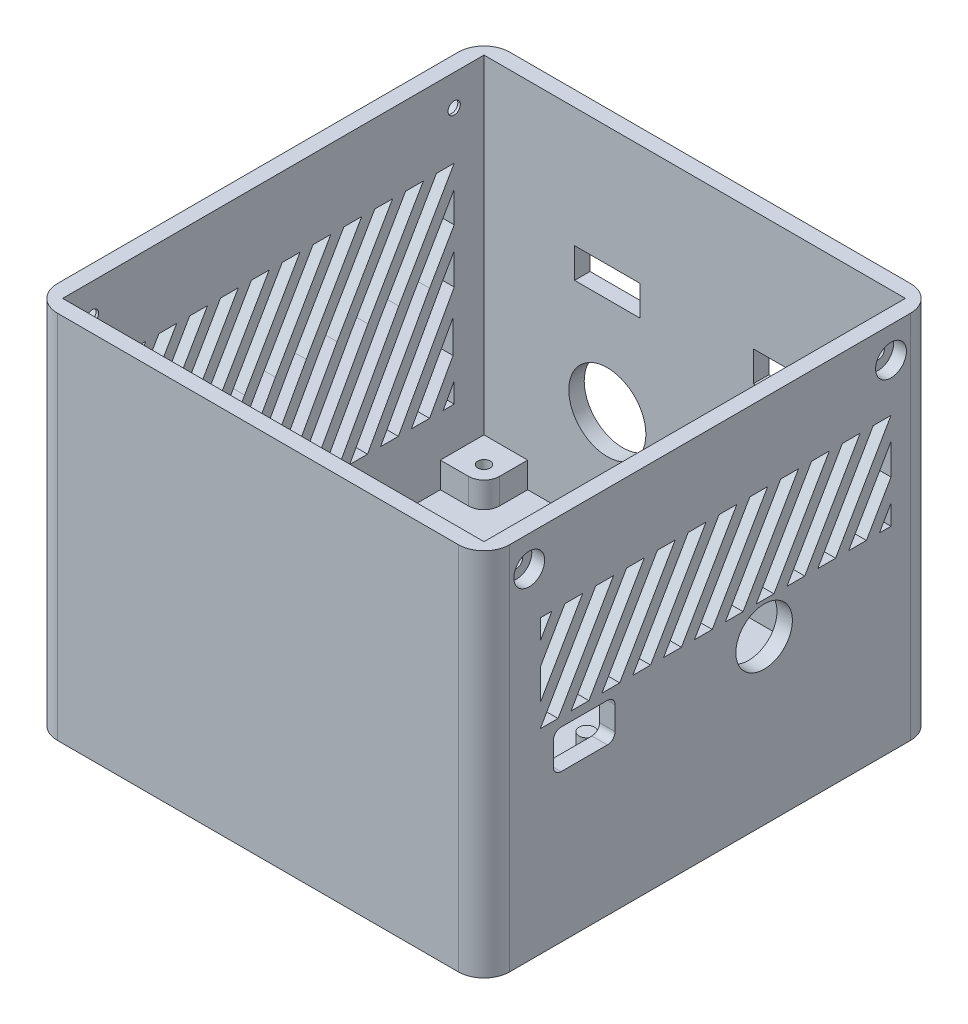
SolidWorks part; units mm, degrees
ref_plane "前基準面" through (0, 0, 0) normal (0, 0, 1) x (1, 0, 0)
ref_plane "上基準面" through (0, 0, 0) normal (0, 1, 0) x (1, 0, 0)
ref_plane "右基準面" through (0, 0, 0) normal (1, 0, 0) x (0, 0, -1)
sketch "草圖1" plane through (0, 0, 0) normal (0, 1, 0) x (1, 0, 0)
  line L5 (-40.3185, 48.6228) -> (47.6815, 48.6228)
  line L6 (-40.3185, 48.6228) -> (-40.3185, -39.3772)
  line L7 (-40.3185, -39.3772) -> (47.6815, -39.3772)
  line L8 (47.6815, 48.6228) -> (47.6815, -39.3772)
  dimension "D1" = 88
  dimension "D2" = 88
extrude "填料-伸長1" add sketch "草圖1" along normal blind 3
sketch "草圖2" plane through (0, 3, 0) normal (0, 1, 0) x (1, 0, 0)
  line L0 (-40.3185, 48.6228) -> (47.6815, 48.6228)
  line L1 (47.6815, 48.6228) -> (47.6815, -39.3772)
  line L2 (47.6815, -39.3772) -> (-40.3185, -39.3772)
  line L3 (-40.3185, -39.3772) -> (-40.3185, 48.6228)
  line L4 (-37.3185, 45.6228) -> (-37.3185, -36.3772)
  line L5 (-37.3185, -36.3772) -> (44.6815, -36.3772)
  line L6 (44.6815, -36.3772) -> (44.6815, 45.6228)
  line L7 (44.6815, 45.6228) -> (-37.3185, 45.6228)
  dimension "D1" = 3
  dimension "D2" = 3
  dimension "D3" = 3
  dimension "D4" = 3
extrude "填料-伸長2" add sketch "草圖2" along normal blind 69
sketch "草圖3" plane through (0, 3, 0) normal (0, 1, 0) x (1, 0, 0)
  line L0 (44.6815, 45.6228) -> (-37.3185, 45.6228) construction
  line L5 (-37.3185, -36.3772) -> (-28.8185, -36.3772)
  line L6 (-37.3185, -36.3772) -> (-37.3185, -27.8772)
  line L7 (-37.3185, -27.8772) -> (-28.8185, -27.8772)
  line L8 (-28.8185, -36.3772) -> (-28.8185, -27.8772)
  line L9 (44.6815, 45.6228) -> (36.1815, 45.6228)
  line L10 (44.6815, 45.6228) -> (44.6815, 37.1228)
  line L11 (44.6815, 37.1228) -> (36.1815, 37.1228)
  line L12 (36.1815, 45.6228) -> (36.1815, 37.1228)
  line L15 (44.6815, -19.3772) -> (36.1815, -19.3772)
  line L16 (36.1815, -27.8772) -> (36.1815, -19.3772)
  line L17 (-37.3185, 45.6228) -> (-37.3185, -36.3772) construction
  line L18 (36.1815, -27.8772) -> (44.6815, -27.8772)
  line L23 (-37.3185, 45.6228) -> (-28.8185, 45.6228)
  line L24 (-37.3185, 45.6228) -> (-37.3185, 37.1228)
  line L25 (-37.3185, 37.1228) -> (-28.8185, 37.1228)
  line L26 (-28.8185, 45.6228) -> (-28.8185, 37.1228)
  line L27 (44.6815, -36.3772) -> (44.6815, 45.6228) construction
  line L28 (44.6815, -27.8772) -> (44.6815, -19.3772)
  circle A0 centre (-17.3185, 25.6228) radius 1.5
  circle A1 centre (2.6815, 25.6228) radius 1.5
  circle A2 centre (22.6815, 25.6228) radius 1.5
  circle A4 centre (22.6815, 5.6228) radius 1.5
  circle A5 centre (2.6815, -14.3772) radius 1.5
  circle A6 centre (22.6815, -14.3772) radius 1.5
  circle A7 centre (-17.3185, 5.6228) radius 1.5
  circle A8 centre (-17.3185, -14.3772) radius 1.5
  circle A9 centre (2.6815, 5.6228) radius 1.5 [skipped]
  circle A10 centre (2.6815, 15.6376) radius 1.5
  dimension "D9" = 3
  dimension "D14" = 3
  dimension "D15" = 40
  dimension "D2" = 8.5
  dimension "D3" = 8.5
  dimension "D4" = 8.5
  dimension "D5" = 8.5
  dimension "D6" = 8.5
  dimension "D7" = 8.5
  dimension "D8" = 8.5
  dimension "D10" = 20
  dimension "D11" = 20
  dimension "D16" = 8.5
  dimension "D12" = 3
  dimension "D13" = 3
extrude "填料-伸長3" add sketch "草圖3" along normal blind 5
sketch "草圖4" plane through (0, 8, 0) normal (0, 1, 0) x (1, 0, 0)
  line L0 (-37.3185, 45.6228) -> (-37.3185, -36.3772) construction
  line L1 (44.6815, 45.6228) -> (-37.3185, 45.6228) construction
  line L2 (-37.3185, -36.3772) -> (44.6815, -36.3772) construction
  line L4 (44.6815, -19.3772) -> (44.6815, 37.1228) construction
  circle A1 centre (-32.3185, -31.3772) radius 1.2
  circle A3 centre (39.6815, 40.6228) radius 1.2
  circle A5 centre (39.6815, -23.3772) radius 1.2
  circle A6 centre (-32.3185, 40.6228) radius 1.2
  dimension "D7" = 5
  dimension "D9" = 2.4
  dimension "D10" = 2.4
  dimension "D2" = 2.4
  dimension "D3" = 5
  dimension "D4" = 5
  dimension "D8" = 5
extrude "除料-伸長1" cut sketch "草圖4" against normal blind 6
fillet "圓角1" radius 5 4 edges at (47.6815, 36, -48.6228) (-40.3185, 36, 39.3772) (-40.3185, 36, -48.6228) (47.6815, 36, 39.3772)
sketch "草圖7" plane through (-40.3185, 0, 0) normal (-1, 0, 0) x (0, 0, 1)
  line L0 (-39.8228, 56.6826) -> (-29.0364, 38)
  line L1 (-39.8228, 56.6826) -> (-36.3587, 56.6826)
  line L2 (-29.0364, 38) -> (-25.5723, 38)
  line L3 (-36.3587, 56.6826) -> (-25.5723, 38)
  line L4 (-48.6228, 0) -> (-48.6228, 72) construction
  line L5 (-33.8228, 56.6826) -> (-23.0364, 38)
  line L6 (-33.8228, 56.6826) -> (-30.3587, 56.6826)
  line L7 (-30.3587, 56.6826) -> (-19.5723, 38)
  line L8 (-23.0364, 38) -> (-19.5723, 38)
  line L9 (-27.8228, 56.6826) -> (-17.0364, 38)
  line L10 (-27.8228, 56.6826) -> (-24.3587, 56.6826)
  line L11 (-24.3587, 56.6826) -> (-13.5723, 38)
  line L12 (-17.0364, 38) -> (-13.5723, 38)
  line L13 (-21.8228, 56.6826) -> (-11.0364, 38)
  line L14 (-21.8228, 56.6826) -> (-18.3587, 56.6826)
  line L15 (-18.3587, 56.6826) -> (-7.5723, 38)
  line L16 (-11.0364, 38) -> (-7.5723, 38)
  line L17 (-15.8228, 56.6826) -> (-5.0364, 38)
  line L18 (-15.8228, 56.6826) -> (-12.3587, 56.6826)
  line L19 (-12.3587, 56.6826) -> (-1.5723, 38)
  line L20 (-5.0364, 38) -> (-1.5723, 38)
  line L21 (-9.8228, 56.6826) -> (0.9636, 38)
  line L22 (-9.8228, 56.6826) -> (-6.3587, 56.6826)
  line L23 (-6.3587, 56.6826) -> (4.4277, 38)
  line L24 (0.9636, 38) -> (4.4277, 38)
  line L25 (-3.8228, 56.6826) -> (6.9636, 38)
  line L26 (-3.8228, 56.6826) -> (-0.3587, 56.6826)
  line L27 (-0.3587, 56.6826) -> (10.4277, 38)
  line L28 (6.9636, 38) -> (10.4277, 38)
  line L29 (2.1772, 56.6826) -> (12.9636, 38)
  line L30 (2.1772, 56.6826) -> (5.6413, 56.6826)
  line L31 (5.6413, 56.6826) -> (16.4277, 38)
  line L32 (12.9636, 38) -> (16.4277, 38)
  line L33 (8.1772, 56.6826) -> (18.9636, 38)
  line L34 (8.1772, 56.6826) -> (11.6413, 56.6826)
  line L35 (11.6413, 56.6826) -> (22.4277, 38)
  line L36 (18.9636, 38) -> (22.4277, 38)
  line L37 (14.1772, 56.6826) -> (24.9636, 38)
  line L38 (14.1772, 56.6826) -> (17.6413, 56.6826)
  line L39 (17.6413, 56.6826) -> (28.4277, 38)
  line L40 (24.9636, 38) -> (28.4277, 38)
  line L52 (-35.0364, 38) -> (-31.5723, 38)
  line L57 (-39.8228, 46.2903) -> (-39.8228, 52.2903)
  line L58 (-39.8228, 46.2903) -> (-35.0364, 38)
  line L59 (-45.8228, 56.6826) -> (-35.0364, 38) [skipped]
  line L60 (-39.8228, 52.2903) -> (-31.5723, 38)
  line L61 (-42.3587, 56.6826) -> (-31.5723, 38) [skipped]
  line L62 (-45.8228, 56.6826) -> (-42.3587, 56.6826) [skipped]
  line L63 (-39.8228, 41.898) -> (-39.8228, 38)
  line L64 (-39.8228, 38) -> (-37.5723, 38)
  line L65 (-51.8228, 56.6826) -> (-41.0364, 38) [skipped]
  line L66 (-39.8228, 41.898) -> (-37.5723, 38)
  line L67 (28.4277, 42.3923) -> (28.4277, 48.3923)
  line L68 (-48.3587, 56.6826) -> (-37.5723, 38) [skipped]
  line L69 (-51.8228, 56.6826) -> (-48.3587, 56.6826) [skipped]
  line L70 (-41.0364, 38) -> (-37.5723, 38) [skipped]
  line L71 (28.4277, 48.3923) -> (23.6413, 56.6826)
  line L72 (20.1772, 56.6826) -> (28.4277, 42.3923)
  line L73 (20.1772, 56.6826) -> (23.6413, 56.6826)
  line L74 (20.1772, 56.6826) -> (30.9636, 38) [skipped]
  line L75 (30.9636, 38) -> (34.4277, 38) [skipped]
  line L76 (23.6413, 56.6826) -> (34.4277, 38) [skipped]
  line L77 (20.1772, 56.6826) -> (23.6413, 56.6826) [skipped]
  line L78 (28.4277, 52.7846) -> (28.4277, 56.6826)
  line L79 (28.4277, 56.6826) -> (26.1772, 56.6826)
  line L80 (26.1772, 56.6826) -> (28.4277, 52.7846)
  line L81 (26.1772, 56.6826) -> (36.9636, 38) [skipped]
  line L82 (36.9636, 38) -> (40.4277, 38) [skipped]
  line L83 (29.6413, 56.6826) -> (40.4277, 38) [skipped]
  line L84 (26.1772, 56.6826) -> (29.6413, 56.6826) [skipped]
  line L86 (-43.6228, 0) -> (34.3772, 0) construction
  dimension "D1" = 3
  dimension "D2" = 120
  dimension "D3" = 8.8
  dimension "D6" = 38
  dimension "D4" = 12
  dimension "D5" = 3
extrude "除料-伸長4" cut sketch "草圖7" against normal through all both and the other way through all
sketch "草圖8" plane through (0, 0, -48.6228) normal (0, 0, -1) x (-1, 0, 0)
  line L0 (-42.6815, 72) -> (-42.6815, 0) construction
  line L1 (-42.6815, 0) -> (35.3185, 0) construction
  line L2 (35.3185, 0) -> (35.3185, 72) construction
  line L3 (-42.6815, 72) -> (35.3185, 72) construction
  line L4 (-25.3665, 48.7) -> (-15.1165, 48.7)
  line L5 (-25.3665, 48.7) -> (-25.3665, 42.85)
  line L6 (-25.3665, 42.85) -> (-15.1165, 42.85)
  line L7 (-15.1165, 48.7) -> (-15.1165, 42.85)
  line L8 (6.9385, 48.7) -> (19.6885, 48.7)
  line L9 (6.9385, 48.7) -> (6.9385, 42.85)
  line L10 (6.9385, 42.85) -> (19.6885, 42.85)
  line L11 (19.6885, 48.7) -> (19.6885, 42.85)
  circle A0 centre (-20.2415, 24) radius 7.5
  circle A1 centre (13.3185, 23.82) radius 7.5
  point P18 (-15.1165, 45.775)
  point P19 (19.6885, 45.775)
  dimension "D2" = 15
  dimension "D3" = 24
  dimension "D4" = 22
  dimension "D5" = 23.82
  dimension "D6" = 15
  dimension "D11" = 5.125
  dimension "D1" = 22.44
  dimension "D7" = 5.85
  dimension "D8" = 5.85
  dimension "D9" = 10.25
  dimension "D10" = 12.75
  dimension "D12" = 6.38
  dimension "D13" = 23.3
  dimension "D14" = 23.3
extrude "除料-伸長5" cut sketch "草圖8" against normal up to next
sketch "草圖9" plane through (47.6815, 0, 0) normal (1, 0, 0) x (0, 0, -1)
  line L0 (43.6228, 0) -> (43.6228, 72) construction
  line L1 (-34.3772, 72) -> (43.6228, 72) construction
  circle A1 centre (15.1328, 31.75) radius 5.5
  dimension "D1" = 28.49
  dimension "D3" = 11
  dimension "D2" = 40.25
extrude "除料-伸長7" cut sketch "草圖9" against normal up to next
sketch "草圖11" plane through (47.6815, 0, 0) normal (1, 0, 0) x (0, 0, -1)
  line L6 (-34.3772, 72) -> (-34.3772, 0) construction
  line L7 (-24.3772, 36.25) -> (-15.3772, 36.25)
  line L8 (-25.8772, 34.75) -> (-25.8772, 30.25)
  line L9 (-24.3772, 28.75) -> (-15.3772, 28.75)
  line L10 (-13.8772, 34.75) -> (-13.8772, 30.25)
  line L11 (-34.3772, 0) -> (43.6228, 0) construction
  arc A4 (-15.3772, 36.25) -> (-13.8772, 34.75) centre (-15.3772, 34.75) cw
  arc A5 (-15.3772, 28.75) -> (-13.8772, 30.25) centre (-15.3772, 30.25) ccw
  arc A6 (-25.8772, 30.25) -> (-24.3772, 28.75) centre (-24.3772, 30.25) ccw
  arc A7 (-24.3772, 36.25) -> (-25.8772, 34.75) centre (-24.3772, 34.75) ccw
  point P10 (-15.3772, 30)
  point P15 (-24.3772, 30)
  point P18 (-15.3772, 35)
  point P28 (-13.8772, 28.75)
  point P31 (-25.8772, 28.75)
  point P34 (-25.8772, 36.25)
  dimension "D5" = 28.75
  dimension "D10" = 1.5
  dimension "D2" = 9
  dimension "D3" = 5
  dimension "D4" = 8.5
  dimension "D6" = 12
  dimension "D7" = 7.5
extrude "除料-伸長9" cut sketch "草圖11" against normal up to next
sketch "草圖12" plane through (-40.3185, 0, 0) normal (-1, 0, 0) x (0, 0, 1)
  line L0 (-35.0364, 38) -> (-22.9609, 16.0785)
  line L1 (-35.0364, 38) -> (-31.5723, 38)
  line L2 (-31.5723, 38) -> (-19.4968, 16.0785)
  line L3 (-19.4968, 16.0785) -> (-22.9609, 16.0785)
  line L4 (-13.4968, 16.0785) -> (-16.9609, 16.0785)
  line L5 (-29.0364, 38) -> (-16.9609, 16.0785)
  line L6 (-29.0364, 38) -> (-25.5723, 38)
  line L7 (-25.5723, 38) -> (-13.4968, 16.0785)
  line L8 (-7.4968, 16.0785) -> (-10.9609, 16.0785)
  line L9 (-23.0364, 38) -> (-10.9609, 16.0785)
  line L10 (-23.0364, 38) -> (-19.5723, 38)
  line L11 (-19.5723, 38) -> (-7.4968, 16.0785)
  line L12 (-1.4968, 16.0785) -> (-4.9609, 16.0785)
  line L13 (-17.0364, 38) -> (-4.9609, 16.0785)
  line L14 (-17.0364, 38) -> (-13.5723, 38)
  line L15 (-13.5723, 38) -> (-1.4968, 16.0785)
  line L16 (4.5032, 16.0785) -> (1.0391, 16.0785)
  line L17 (-11.0364, 38) -> (1.0391, 16.0785)
  line L18 (-11.0364, 38) -> (-7.5723, 38)
  line L19 (-7.5723, 38) -> (4.5032, 16.0785)
  line L20 (10.5032, 16.0785) -> (7.0391, 16.0785)
  line L21 (-5.0364, 38) -> (7.0391, 16.0785)
  line L22 (-5.0364, 38) -> (-1.5723, 38)
  line L23 (-1.5723, 38) -> (10.5032, 16.0785)
  line L24 (16.5032, 16.0785) -> (13.0391, 16.0785)
  line L25 (0.9636, 38) -> (13.0391, 16.0785)
  line L26 (0.9636, 38) -> (4.4277, 38)
  line L27 (4.4277, 38) -> (16.5032, 16.0785)
  line L28 (22.5032, 16.0785) -> (19.0391, 16.0785)
  line L29 (6.9636, 38) -> (19.0391, 16.0785)
  line L30 (6.9636, 38) -> (10.4277, 38)
  line L31 (10.4277, 38) -> (22.5032, 16.0785)
  line L32 (-37.5723, 38) -> (-25.4968, 16.0785)
  line L33 (-25.4968, 16.0785) -> (-28.9568, 16.0785)
  line L34 (-28.9568, 16.0785) -> (-39.8228, 35.8043)
  line L35 (-39.8228, 35.8043) -> (-39.8228, 38)
  line L36 (-39.8228, 38) -> (-37.5723, 38)
  line L37 (-31.4968, 16.0785) -> (-35.0308, 16.0785)
  line L38 (-31.4968, 16.0785) -> (-39.5997, 30.7883)
  line L39 (-35.0308, 16.0785) -> (-39.5997, 24.3728)
  line L40 (-39.5997, 24.3728) -> (-39.5997, 30.7883)
  line L44 (-39.8228, 16.0785) -> (-39.8228, 19.9785)
  line L48 (-39.8228, 19.9785) -> (-37.6745, 16.0785)
  line L49 (-37.6745, 16.0785) -> (-39.8228, 16.0785)
  line L50 (12.9636, 38) -> (24.9651, 16.2128)
  line L51 (16.4277, 38) -> (28.4292, 16.2128)
  line L52 (28.4292, 16.2128) -> (24.9651, 16.2128)
  line L53 (12.9636, 38) -> (16.4277, 38)
  line L54 (18.9636, 38) -> (28.5183, 20.6547)
  line L55 (18.9636, 38) -> (22.4277, 38)
  line L56 (22.4277, 38) -> (28.5183, 26.9434)
  line L57 (28.5183, 26.9434) -> (28.5183, 20.6547)
  line L58 (24.9636, 38) -> (28.729, 31.1645)
  line L59 (28.729, 31.1645) -> (28.4277, 38)
  line L60 (28.4277, 38) -> (24.9636, 38)
  line L61 (-23.0364, 38) -> (-33.8228, 56.6826) construction
  dimension "D4" = 4.4
  dimension "D6" = 3.9
  dimension "D1" = 8
extrude "除料-伸長10" cut sketch "草圖12" against normal up to next
sketch "草圖13" plane through (-40.3185, 0, 0) normal (-1, 0, 0) x (0, 0, 1)
  line L0 (-43.6228, 72) -> (34.3772, 72) construction
  line L1 (-48.6228, 0) -> (-48.6228, 72) construction
  line L2 (39.3772, 72) -> (39.3772, 0) construction
  circle A0 centre (-39.8228, 66) radius 1.2
  circle A1 centre (30.5772, 66) radius 1.2
  dimension "D4" = 8.8
  dimension "D5" = 2.4
  dimension "D6" = 2.4
  dimension "D1" = 6
  dimension "D2" = 8.8
  dimension "D3" = 6
extrude "除料-伸長11" cut sketch "草圖13" against normal through all both and the other way through all
sketch "草圖14" plane through (-40.3185, 0, 0) normal (-1, 0, 0) x (0, 0, 1)
  circle A0 centre (-39.8228, 66) radius 3
  circle A1 centre (30.5772, 66) radius 3
  dimension "D1" = 6
  dimension "D2" = 6
extrude "除料-伸長12" cut sketch "草圖14" against normal blind 2.5
sketch "草圖15" plane through (47.6815, 0, 0) normal (1, 0, 0) x (0, 0, -1)
  circle A0 centre (-30.5772, 66) radius 3
  circle A1 centre (39.8228, 66) radius 3
  dimension "D1" = 6
  dimension "D2" = 6
extrude "除料-伸長13" cut sketch "草圖15" against normal blind 2.5
fillet "圓角2" radius 3 5 edges at (-28.8185, 5.5, -37.1228) (36.1815, 5.5, -37.1228) (-28.8185, 5.5, 27.8772) (36.1815, 5.5, 27.8772) (36.1815, 5.5, 19.3772)
